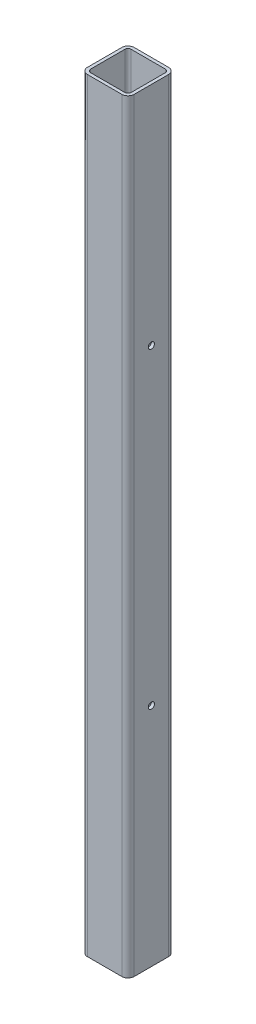
SolidWorks part; units mm, degrees
material "AISI 1010 钢，热轧条材"
ref_plane "前视基准面" through (0, 0, 0) normal (0, 0, 1) x (1, 0, 0)
ref_plane "上视基准面" through (0, 0, 0) normal (0, 1, 0) x (1, 0, 0)
ref_plane "右视基准面" through (0, 0, 0) normal (1, 0, 0) x (0, 0, -1)
sketch "草图1" plane through (0, 0, 0) normal (0, 1, 0) x (1, 0, 0)
  line L0 (-11, -13) -> (11, -13)
  line L1 (-11, -15) -> (11, -15)
  line L2 (-15, -11) -> (-15, 11)
  line L3 (-11, 15) -> (11, 15)
  line L4 (15, -11) -> (15, 11)
  line L5 (13, -11) -> (13, 11)
  line L6 (-11, 13) -> (11, 13)
  line L7 (-13, -11) -> (-13, 11)
  arc A0 (-11, -15) -> (-15, -11) centre (-11, -11) cw
  arc A1 (11, -15) -> (15, -11) centre (11, -11) ccw
  arc A2 (11, 15) -> (15, 11) centre (11, 11) cw
  arc A3 (-15, 11) -> (-11, 15) centre (-11, 11) cw
  arc A4 (11, -13) -> (13, -11) centre (11, -11) ccw
  arc A5 (11, 13) -> (13, 11) centre (11, 11) cw
  arc A6 (-13, 11) -> (-11, 13) centre (-11, 11) cw
  arc A7 (-11, -13) -> (-13, -11) centre (-11, -11) cw
extrude "凸台-拉伸1" add sketch "草图1" along normal mid plane 490
sketch "草图2" plane through (0, 0, 0) normal (1, 0, 0) x (0, 0, -1)
  line L0 (-15, 0) -> (15, 0) construction
  line L1 (-15, 245) -> (-15, -245) construction
  line L2 (15, 245) -> (15, -245) construction
  line L3 (-11, -245) -> (11, -245) construction
  circle A0 centre (0, -100) radius 2
  circle A2 centre (0, 100) radius 2
  dimension "D1" = 4
  dimension "D2" = 145
extrude "切除-拉伸1" cut sketch "草图2" along normal up to next
sketch "草图3" plane through (0, 0, 0) normal (1, 0, 0) x (0, 0, -1)
  circle A0 centre (0, -100) radius 2 construction
  circle A1 centre (0, 100) radius 2 construction
  circle A2 centre (0, -100) radius 2 construction
  circle A3 centre (0, 100) radius 2 construction
  circle A4 centre (0, -100) radius 6
  circle A5 centre (0, 100) radius 6
  dimension "D1" = 4
extrude "切除-拉伸2" cut sketch "草图3" against normal up to next
sketch "草图4" plane through (0, 0, -15) normal (0, 0, 1) x (1, 0, 0)
  line L0 (15, 245) -> (15, -245) construction
  line L1 (15, -85) -> (0, -85)
  line L2 (15, -85) -> (15, -115)
  line L3 (15, -115) -> (0, -115)
  line L4 (0, -85) -> (0, -115)
  line L5 (-11, -245) -> (11, -245) construction
  line L6 (-15, 0) -> (15, 0) construction
  line L7 (-15, 245) -> (-15, -245) construction
  line L8 (0, 85) -> (0, 115)
  line L9 (15, 115) -> (0, 115)
  line L10 (15, 85) -> (15, 115)
  line L11 (15, 85) -> (0, 85)
  point P6 (15, -100)
  dimension "D1" = 145
  dimension "D2" = 30
  dimension "D3" = 15
extrude "切除-拉伸3" cut sketch "草图4" along normal blind 2
